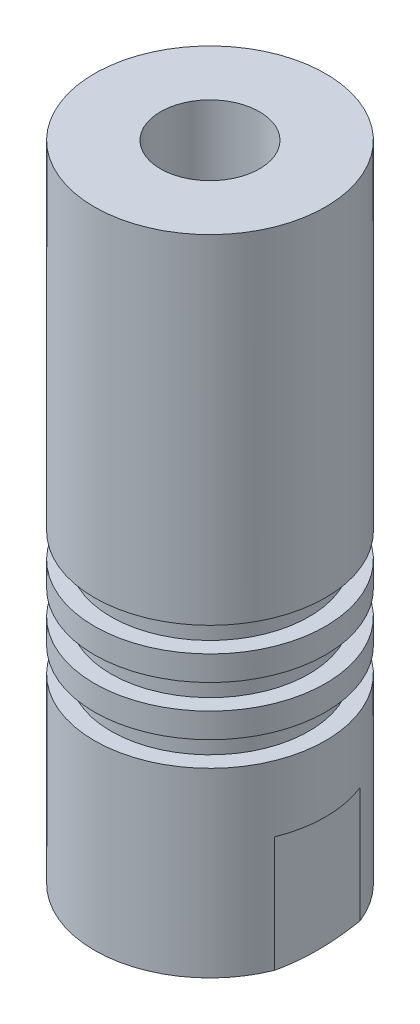
SolidWorks part; units mm, degrees
material "Gomma"
ref_plane "Piano frontale" through (0, 0, 0) normal (0, 0, 1) x (1, 0, 0)
ref_plane "Piano superiore" through (0, 0, 0) normal (0, 1, 0) x (1, 0, 0)
ref_plane "Piano destro" through (0, 0, 0) normal (1, 0, 0) x (0, 0, -1)
sketch "Schizzo1" plane through (0, 0, 0) normal (0, 0, 1) x (1, 0, 0)
  line L0 (0, 0) -> (-5, 0)
  line L1 (-5, 0) -> (-8, 1.5)
  line L2 (-8, 1.5) -> (-8, 12)
  line L3 (-8, 12) -> (-6, 12)
  line L4 (-6, 12) -> (-6, 13.5)
  line L5 (-6, 13.5) -> (-8, 13.5)
  line L6 (-8, 13.5) -> (-8, 15)
  line L7 (-8, 15) -> (-6, 15)
  line L8 (-6, 15) -> (-6, 16.5)
  line L9 (-6, 16.5) -> (-8, 16.5)
  line L10 (-8, 16.5) -> (-8, 18)
  line L11 (-8, 18) -> (-6, 18)
  line L12 (-6, 18) -> (-6, 19.5)
  line L13 (-6, 19.5) -> (-8, 19.5)
  line L14 (-8, 19.5) -> (-8, 30.6)
  line L15 (-8, 30.6) -> (-6, 30.6)
  line L16 (-6, 30.6) -> (-6, 35.2)
  line L17 (-6, 35.2) -> (-8, 35.2)
  line L18 (-8, 35.2) -> (-8, 40)
  line L19 (-8, 40) -> (0, 40)
  line L20 (0, 40) -> (0, 0)
  line L21 (0, 129.4074) -> (0, -17.2322) construction
  dimension "D1" = 1.5
  dimension "D2" = 16
  dimension "D3" = 2
  dimension "D4" = 40
  dimension "D5" = 12
  dimension "D6" = 4.8
  dimension "D7" = 4.6
  dimension "D8" = 1.5
  dimension "D9" = 6
  dimension "D10" = 10
revolve "Rivoluzione1" add sketch "Schizzo1" angle 360 about L21
sketch "Schizzo2" plane through (0, 0, 0) normal (0, 0, 1) x (1, 0, 0)
  line L0 (-8, 8) -> (-6.5, 8)
  line L1 (-6.5, 8) -> (-6.5, 0)
  line L2 (-6.5, 0) -> (-8, 0)
  line L3 (-8, 0) -> (-8, 8)
  line L4 (6.5, 8) -> (6.5, 0)
  line L5 (6.5, 0) -> (8, 0)
  line L6 (8, 0) -> (8, 8)
  line L7 (8, 8) -> (6.5, 8)
  line L8 (0, 0) -> (0, 9.0399) construction
  line L9 (-5, 0) -> (5, 0) construction
  line L10 (8, 40) -> (-8, 40) construction
  line L11 (8, 1.5) -> (8, 12) construction
  line L12 (-8, 12) -> (-8, 1.5) construction
  dimension "D1" = 32
  dimension "D2" = 1.5
extrude "Taglio-Estrusione1" cut sketch "Schizzo2" against normal up to next and the other way up to next
sketch "Schizzo7" plane through (0, 40, 0) normal (0, 1, 0) x (1, 0, 0)
  circle A0 centre (0, 0) radius 3
extrude "Taglio-Estrusione2" cut sketch "Schizzo7" against normal through all
hole_wizard "Foro filettato M8-1" positions "Schizzo9" profile "Schizzo8" tap size "M8" standard "ISO"
sketch "Schizzo9" plane through (0, 0, 0) normal (0, -1, 0) x (-1, 0, 0)
  point P0 (0, 0)
sketch "Schizzo8" plane through (0, 0, 0) normal (1, 0, 0) x (0, 0, -1)
  line L0 (0, 0) -> (0, 14.0429)
  line L1 (0, 14.0429) -> (3.4, 12)
  line L2 (3.4, 12) -> (3.4, 0)
  line L5 (3.4, 0) -> (0, 0)
  line L10 (0, 14.0429) -> (-3.4, 12) construction
  line L11 (0, -6.35) -> (0, 107.95) construction
  dimension "Tap Drill Dia." = 6.8
  dimension "Tap Drill Depth" = 12
  dimension "Drill Angle" = 118
cosmetic thread "Filettatura del foro3" parameters "D1"=12, "D2"=8
sketch "Schizzo10" plane through (0, 40, 0) normal (0, 1, 0) x (1, 0, 0)
  circle A0 centre (0, 0) radius 7
  circle A1 centre (0, 0) radius 8
  dimension "D1" = 14
extrude "Taglio-Estrusione3" cut sketch "Schizzo10" against normal up to surface (40 mm away) up to face at (0, 0, -3.4)
sketch "Schizzo11" plane through (0, 30.6, 0) normal (0, 1, 0) x (1, 0, 0)
  circle A0 centre (0, 0) radius 7
extrude "Estrusione-Estrusione1" add sketch "Schizzo11" along normal up to surface (4.6 mm away) up to face at (0, 35.2, 6)
sketch "Schizzo12" plane through (0, 35.2, 0) normal (0, 1, 0) x (1, 0, 0)
  circle A0 centre (0, 0) radius 3
extrude "Taglio-Estrusione4" cut sketch "Schizzo12" against normal blind 5
